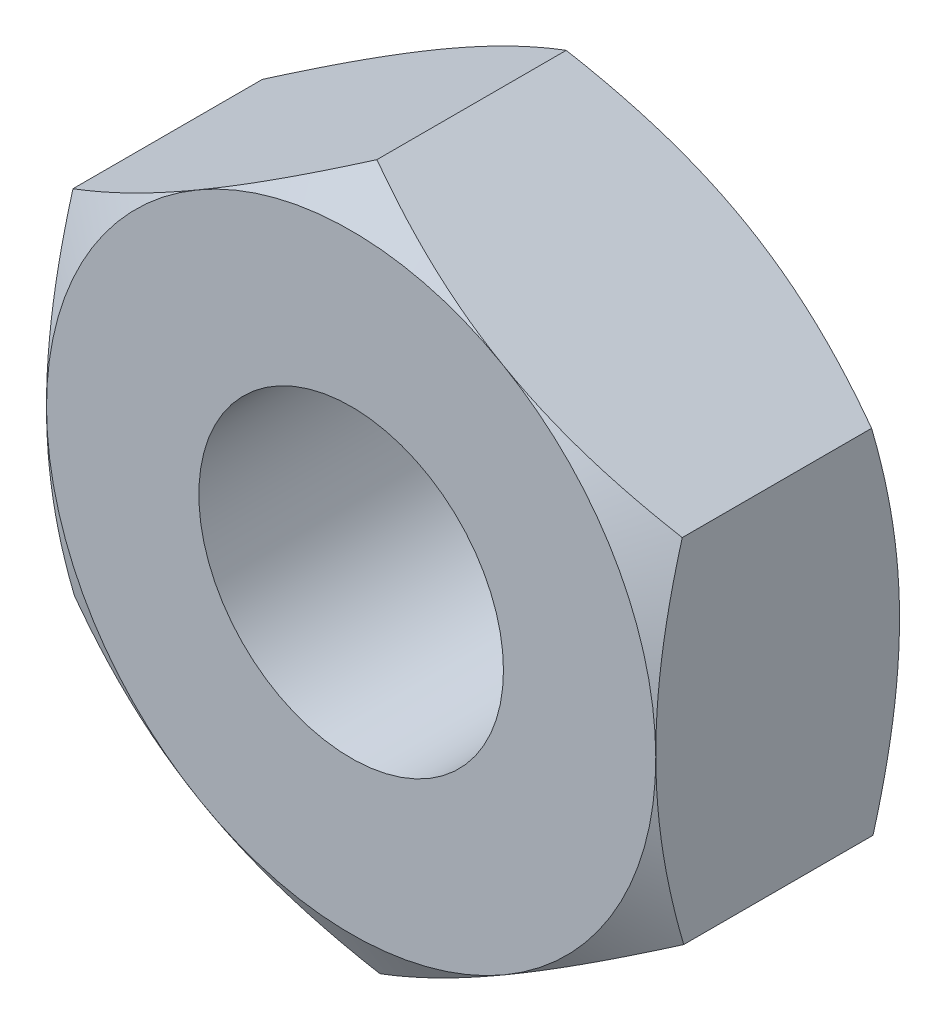
SolidWorks part; units mm, degrees
ref_plane "Front Plane" through (0, 0, 0) normal (0, 0, 1) x (1, 0, 0)
ref_plane "Top Plane" through (0, 0, 0) normal (0, 1, 0) x (1, 0, 0)
ref_plane "Right Plane" through (0, 0, 0) normal (1, 0, 0) x (0, 0, -1)
sketch "Sketch1" plane through (0, 0, 0) normal (0, 0, 1) x (1, 0, 0)
  line L1 (10.0235, -5.7326) -> (9.9763, 5.8143)
  line L2 (9.9763, 5.8143) -> (-0.0472, 11.5469)
  line L3 (-0.0472, 11.5469) -> (-10.0235, 5.7326)
  line L4 (-10.0235, 5.7326) -> (-9.9763, -5.8143)
  line L5 (-9.9763, -5.8143) -> (0.0472, -11.5469)
  line L6 (0.0472, -11.5469) -> (10.0235, -5.7326)
  circle A0 centre (0, 0) radius 10 construction
  circle A1 centre (0, 0) radius 5
  dimension "D1" = 20
extrude "Boss-Extrude1" add sketch "Sketch1" along normal mid plane 8
sketch "Sketch2" plane through (0, 0, -4) normal (0, 0, -1) x (-1, 0, 0)
  circle A0 centre (0, 0) radius 10
extrude "Cut-Extrude1" cut sketch "Sketch2" against normal blind 8 draft 60 flip side to cut
mirror "Mirror1" about plane through (0, 0, 0) normal (0, 0, 1) of "Cut-Extrude1"
